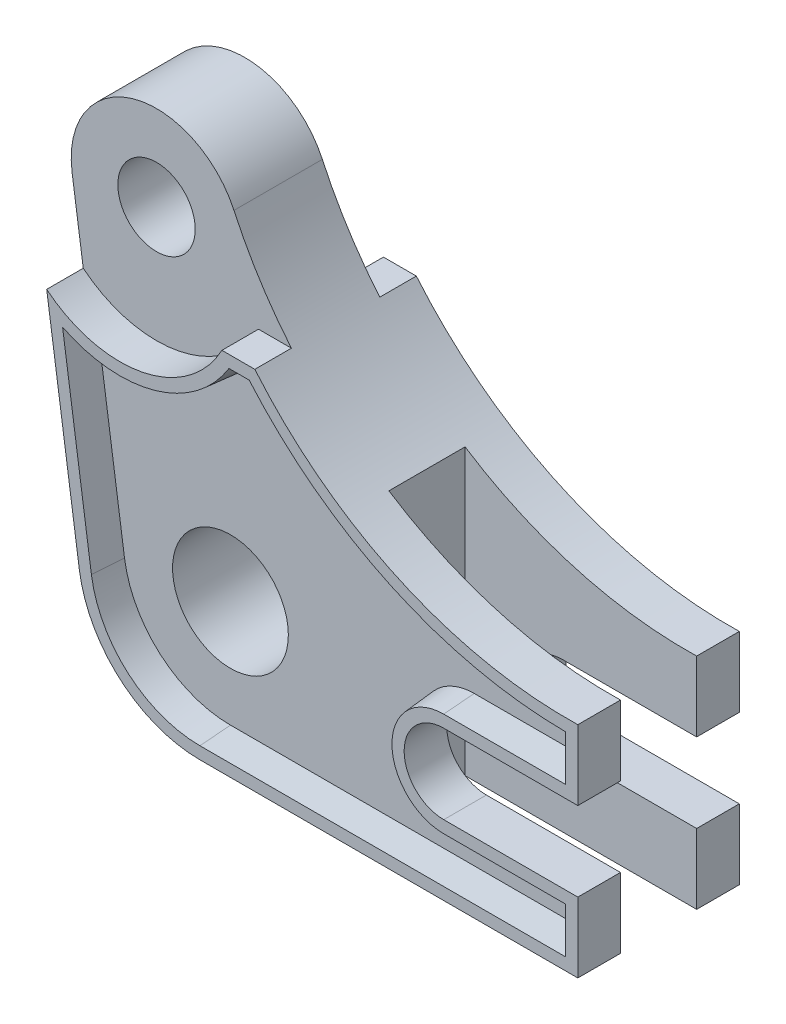
SolidWorks part; units mm, degrees
material "AISI 1020"
ref_plane "Front Plane" through (0, 0, 0) normal (0, 0, 1) x (1, 0, 0)
ref_plane "Top Plane" through (0, 0, 0) normal (0, 1, 0) x (1, 0, 0)
ref_plane "Right Plane" through (0, 0, 0) normal (1, 0, 0) x (0, 0, -1)
sketch "Sketch3" plane through (0, 0, 0) normal (0, 0, 1) x (1, 0, 0)
  line L0 (0, 0) -> (-13.1295, 49) construction
  line L1 (-26.9861, 47.0014) -> (-19.7952, -2.8551)
  line L2 (0, -20) -> (62, -20)
  line L3 (62, -20) -> (62, 16)
  line L4 (62, -2) -> (40, -2) construction
  line L7 (62, -8.5) -> (40, -8.5)
  line L8 (62, 4.5) -> (40, 4.5)
  circle A0 centre (0, 0) radius 9.5
  circle A1 centre (-13.1295, 49) radius 6.35
  circle A2 centre (0, 0) radius 20
  circle A3 centre (-13.1295, 49) radius 14
  arc A4 (-0.421, 54.8732) -> (62, 16) centre (60.398, 82.9808) ccw
  arc A7 (62, -8.5) -> (62, 4.5) centre (62, -2) ccw
  arc A8 (40, 4.5) -> (40, -8.5) centre (40, -2) ccw
  point P16 (51, -2)
  dimension "D1" = 12.7
  dimension "D2" = 19
  dimension "D4" = 40
  dimension "D5" = 28
  dimension "D7" = 67
  dimension "D11" = 22
  dimension "D9" = 6.5
  dimension "D3" = 15
  dimension "D6" = 49
  dimension "D8" = 36
  dimension "D10" = 62
extrude "Boss-Extrude6" add sketch "Sketch3" along normal blind 26.5 contours A8 L8 L3 A4 A3 L1 A2 L2 L7 | A3 A1 | A2 A0
sketch "Sketch7" plane through (0, 0, 0) normal (0, 0, 1) x (1, 0, 0)
  line L1 (62, -20) -> (24, -20)
  line L2 (62, -20) -> (62, 51.1553)
  line L3 (62, 51.1553) -> (24, 51.1553)
  line L4 (24, -20) -> (24, 51.1553)
  dimension "D1" = 38
  dimension "D2" = 71.1553
extrude "Cut-Extrude5" cut sketch "Sketch7" along normal blind 12.5 from offset 7
sketch "Sketch8" plane through (0, 0, 26.5) normal (0, 0, 1) x (1, 0, 0)
  line L0 (-26.9861, 47.0014) -> (-19.7952, -2.8551) construction
  line L1 (3.6037, 40) -> (9.0011, 40)
  arc A0 (-25.1524, 34.2877) -> (3.6037, 40) centre (-13.1295, 49) ccw
  arc A1 (-0.421, 54.8732) -> (62, 16) centre (60.398, 82.9808) ccw construction
  dimension "D1" = 19
  dimension "D2" = 9
extrude "Cut-Extrude6" cut sketch "Sketch8" against normal blind 6 and the other way through all
sketch "Sketch9" plane through (0, 0, 0) normal (0, 0, -1) x (-1, 0, 0)
  line L0 (26.9861, 47.0014) -> (19.7952, -2.8551) construction
  line L1 (-3.6037, 40) -> (-9.0011, 40)
  arc A0 (25.1524, 34.2877) -> (-3.6037, 40) centre (13.1295, 49) cw
  arc A1 (-62, 16) -> (0.421, 54.8732) centre (-60.398, 82.9808) ccw construction
  dimension "D1" = 19
  dimension "D2" = 9
extrude "Cut-Extrude8" cut sketch "Sketch9" against normal blind 6 and the other way through all flip side to cut
sketch "Sketch11" plane through (0, 0, 0) normal (0, 0, 1) x (1, 0, 0)
  line L28 (9.0011, 40) -> (3.6037, 40)
  line L29 (-25.1524, 34.2877) -> (-19.7952, -2.8551)
  line L30 (0, -20) -> (62, -20)
  line L31 (62, -20) -> (62, -8.5)
  line L32 (62, -8.5) -> (40, -8.5)
  line L33 (40, 4.5) -> (62, 4.5)
  line L34 (62, 4.5) -> (62, 16)
  line L35 (9.0011, 40) -> (3.6037, 40)
  line L36 (-25.1524, 34.2877) -> (-19.7952, -2.8551)
  line L37 (0, -20) -> (62, -20)
  line L38 (62, -20) -> (62, -8.5)
  line L39 (62, -8.5) -> (40, -8.5)
  line L40 (40, 4.5) -> (62, 4.5)
  line L41 (62, 4.5) -> (62, 16)
  line L77 (8.0748, 38) -> (4.759, 38)
  line L78 (-22.5464, 30.2298) -> (-17.8156, -2.5696)
  line L79 (0, -18) -> (60, -18)
  line L80 (60, -18) -> (60, -10.5)
  line L81 (60, -10.5) -> (40, -10.5)
  line L82 (40, 6.5) -> (60, 6.5)
  line L83 (60, 6.5) -> (60, 13.982)
  line L84 (8.0748, 38) -> (4.759, 38)
  line L85 (-22.5464, 30.2298) -> (-17.8156, -2.5696)
  line L86 (0, -18) -> (60, -18)
  line L87 (60, -18) -> (60, -10.5)
  line L88 (60, -10.5) -> (40, -10.5)
  line L89 (40, 6.5) -> (60, 6.5)
  line L90 (60, 6.5) -> (60, 13.982)
  arc A16 (-25.1524, 34.2877) -> (3.6037, 40) centre (-13.1295, 49) ccw
  arc A17 (-19.7952, -2.8551) -> (0, -20) centre (0, 0) ccw
  arc A18 (40, 4.5) -> (40, -8.5) centre (40, -2) ccw
  arc A19 (9.0011, 40) -> (62, 16) centre (60.398, 82.9808) ccw
  arc A20 (-25.1524, 34.2877) -> (3.6037, 40) centre (-13.1295, 49) ccw
  arc A21 (-19.7952, -2.8551) -> (0, -20) centre (0, 0) ccw
  arc A22 (40, 4.5) -> (40, -8.5) centre (40, -2) ccw
  arc A23 (9.0011, 40) -> (62, 16) centre (60.398, 82.9808) ccw
  arc A44 (-22.5464, 30.2298) -> (4.759, 38) centre (-13.1295, 49) ccw
  arc A45 (-17.8156, -2.5696) -> (0, -18) centre (0, 0) ccw
  arc A46 (40, 6.5) -> (40, -10.5) centre (40, -2) ccw
  arc A47 (8.0748, 38) -> (60, 13.982) centre (60.398, 82.9808) ccw
  arc A48 (-22.5464, 30.2298) -> (4.759, 38) centre (-13.1295, 49) ccw
  arc A49 (-17.8156, -2.5696) -> (0, -18) centre (0, 0) ccw
  arc A50 (40, 6.5) -> (40, -10.5) centre (40, -2) ccw
  arc A51 (8.0748, 38) -> (60, 13.982) centre (60.398, 82.9808) ccw
  dimension "D1" = 0
  dimension "D2" = 2
extrude "Cut-Extrude10" cut sketch "Sketch11" along normal blind 5 draft 5 contours L84 A48 L85 A49 L86 L87 L88 A50 L89 L90 A51
sketch "Sketch12" plane through (0, 0, 26.5) normal (0, 0, 1) x (1, 0, 0)
  line L0 (8.0748, 38) -> (4.759, 38)
  line L1 (-22.5464, 30.2298) -> (-17.8156, -2.5696)
  line L2 (0, -18) -> (60, -18)
  line L3 (60, -18) -> (60, -10.5)
  line L4 (60, -10.5) -> (40, -10.5)
  line L5 (40, 6.5) -> (60, 6.5)
  line L6 (60, 6.5) -> (60, 13.982)
  line L7 (9.0011, 40) -> (3.6037, 40)
  line L8 (-25.1524, 34.2877) -> (-19.7952, -2.8551)
  line L9 (0, -20) -> (62, -20)
  line L10 (62, -20) -> (62, -8.5)
  line L11 (62, -8.5) -> (40, -8.5)
  line L12 (40, 4.5) -> (62, 4.5)
  line L13 (62, 4.5) -> (62, 16)
  line L14 (9.0011, 40) -> (3.6037, 40)
  line L15 (-25.1524, 34.2877) -> (-19.7952, -2.8551)
  line L16 (0, -20) -> (62, -20)
  line L17 (62, -20) -> (62, -8.5)
  line L18 (62, -8.5) -> (40, -8.5)
  line L19 (40, 4.5) -> (62, 4.5)
  line L20 (62, 4.5) -> (62, 16)
  arc A0 (-22.5464, 30.2298) -> (4.759, 38) centre (-13.1295, 49) ccw
  arc A1 (-17.8156, -2.5696) -> (0, -18) centre (0, 0) ccw
  arc A2 (40, 6.5) -> (40, -10.5) centre (40, -2) ccw
  arc A3 (8.0748, 38) -> (60, 13.982) centre (60.398, 82.9808) ccw
  arc A4 (-25.1524, 34.2877) -> (3.6037, 40) centre (-13.1295, 49) ccw
  arc A5 (-19.7952, -2.8551) -> (0, -20) centre (0, 0) ccw
  arc A6 (40, 4.5) -> (40, -8.5) centre (40, -2) ccw
  arc A7 (9.0011, 40) -> (62, 16) centre (60.398, 82.9808) ccw
  arc A8 (-25.1524, 34.2877) -> (3.6037, 40) centre (-13.1295, 49) ccw
  arc A9 (-19.7952, -2.8551) -> (0, -20) centre (0, 0) ccw
  arc A10 (40, 4.5) -> (40, -8.5) centre (40, -2) ccw
  arc A11 (9.0011, 40) -> (62, 16) centre (60.398, 82.9808) ccw
  dimension "D1" = 0
  dimension "D2" = 2
extrude "Cut-Extrude11" cut sketch "Sketch12" against normal blind 5 draft 5 contours L0 A0 L1 A1 L2 L3 L4 A2 L5 L6 A3
equation "\"A\" = 62MM"
equation "\"B\"= 20MM"
equation "\"C\"= 26.5MM"
